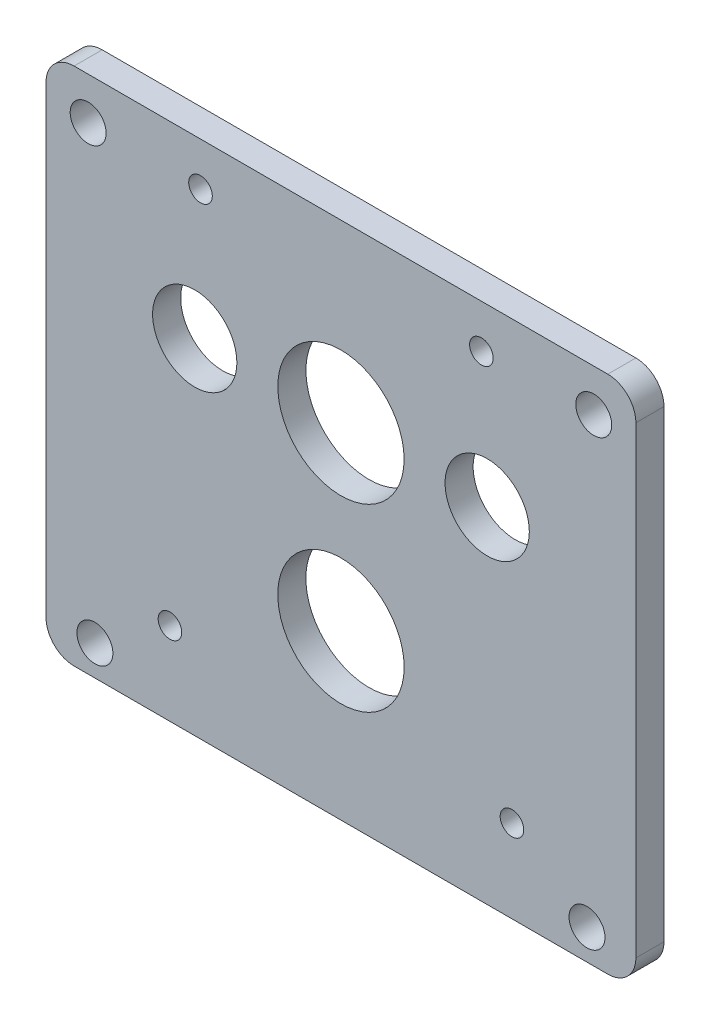
SolidWorks part; units mm, degrees
material "6061 Alloy"
ref_plane "Front Plane" through (0, 0, 0) normal (0, 0, 1) x (1, 0, 0)
ref_plane "Top Plane" through (0, 0, 0) normal (0, 1, 0) x (1, 0, 0)
ref_plane "Right Plane" through (0, 0, 0) normal (1, 0, 0) x (0, 0, -1)
sketch "Sketch1" plane through (0, 0, 0) normal (0, 0, 1) x (1, 0, 0)
  line L0 (-33.0581, 40.7162) -> (33.0581, 40.7162) construction
  line L1 (0, 40.7162) -> (0, 0) construction
  line L2 (-31.75, 70.5866) -> (31.75, 70.5866) construction
  line L3 (-66.675, 80.4164) -> (66.675, 80.4164)
  line L4 (-66.675, 80.4164) -> (-66.675, -37.0586)
  line L5 (-66.675, -37.0586) -> (66.675, -37.0586)
  line L6 (66.675, 80.4164) -> (66.675, -37.0586)
  line L7 (-66.675, 80.4164) -> (66.675, -37.0586) construction
  line L8 (-66.675, -37.0586) -> (66.675, 80.4164) construction
  line L9 (-38.6588, -18.3134) -> (38.6588, -18.3134) construction
  line L10 (0, 70.5866) -> (0, -18.3134) construction
  circle A0 centre (0, 40.7162) radius 26.67 construction
  circle A1 centre (0, 40.7162) radius 25.4 construction
  circle A2 centre (-33.0581, 40.7162) radius 8.89 construction
  circle A3 centre (33.0581, 40.7162) radius 7.62 construction
  circle A4 centre (33.0581, 40.7162) radius 8.89 construction
  circle A5 centre (-33.0581, 40.7162) radius 7.62 construction
  circle A6 centre (0, 40.7162) radius 16.51 construction
  circle A7 centre (0, 40.7162) radius 15.24 construction
  circle A8 centre (0, 0) radius 26.67 construction
  circle A9 centre (0, 0) radius 25.4 construction
  circle A10 centre (0, 40.7162) radius 14.2748
  circle A11 centre (33.0581, 40.7162) radius 9.525
  circle A12 centre (-33.0581, 40.7162) radius 9.525
  circle A13 centre (-33.0581, 40.7162) radius 32.004 construction
  circle A14 centre (33.0581, 40.7162) radius 32.004 construction
  circle A15 centre (-33.0581, 40.7162) radius 25.4 construction
  circle A16 centre (33.0581, 40.7162) radius 25.4 construction
  circle A17 centre (-57.15, 70.8914) radius 9.525 construction
  circle A18 centre (57.15, 70.8914) radius 9.525 construction
  circle A21 centre (0, 0) radius 14.2875
  circle A22 centre (-57.15, 70.8914) radius 4.064
  circle A23 centre (-55.626, -30.2006) radius 4.064
  circle A24 centre (57.15, 70.8914) radius 4.064
  circle A25 centre (55.626, -30.2006) radius 4.064
  circle A26 centre (38.6588, -18.3134) radius 2.667
  circle A27 centre (-38.6588, -18.3134) radius 2.667
  circle A28 centre (-31.75, 70.5866) radius 2.667
  circle A29 centre (31.75, 70.5866) radius 2.667
  point P31 (0, 21.6789)
  dimension "D1" = 53.34
  dimension "D2" = 50.8
  dimension "D3" = 15.24
  dimension "D4" = 17.78
  dimension "D6" = 30.48
  dimension "D7" = 33.02
  dimension "D9" = 28.5496
  dimension "D10" = 19.05
  dimension "D11" = 64.008
  dimension "D12" = 50.8
  dimension "D13" = 19.05
  dimension "D15" = 63.5
  dimension "D16" = 5.334
  dimension "D17" = 28.575
  dimension "D21" = 8.128
  dimension "D22" = 55.626
  dimension "D5" = 66.1162
  dimension "D8" = 40.7162
  dimension "D14" = 133.35
  dimension "4" = 117.475
  dimension "D18" = 88.9
  dimension "D19" = 77.3176
  dimension "D20" = 18.3134
  dimension "D23" = 55.626
  dimension "D24" = 30.2006
  dimension "D25" = 30.2006
  dimension "D26" = 80.4164
extrude "Boss-Extrude1" add sketch "Sketch1" along normal mid plane 6.35
fillet "Fillet1" radius 6.35 4 edges at (66.675, 80.4164, 0) (66.675, -37.0586, 0) (-66.675, -37.0586, 0) (-66.675, 80.4164, 0)
